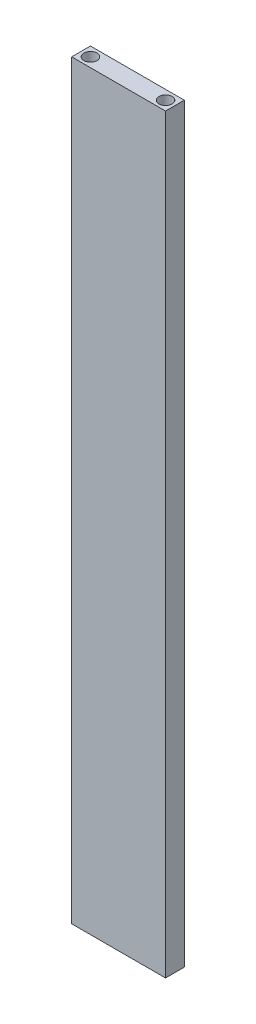
SolidWorks part; units mm, degrees
ref_plane "Front Plane" through (0, 0, 0) normal (0, 0, 1) x (1, 0, 0)
ref_plane "Top Plane" through (0, 0, 0) normal (0, 1, 0) x (1, 0, 0)
ref_plane "Right Plane" through (0, 0, 0) normal (1, 0, 0) x (0, 0, -1)
sketch "Sketch1" plane through (0, 0, 0) normal (0, 1, 0) x (1, 0, 0)
  line L1 (0, 0) -> (-20, 0)
  line L2 (0, 0) -> (0, -4)
  line L3 (0, -4) -> (-20, -4)
  line L4 (-20, 0) -> (-20, -4)
  dimension "D1" = 20
  dimension "D2" = 4
extrude "Boss-Extrude1" add sketch "Sketch1" along normal blind 160
sketch "Sketch2" plane through (0, 0, 0) normal (0, -1, 0) x (-1, 0, 0)
  line L0 (20, 0) -> (20, -4) construction
  line L1 (18, -2) -> (2, -2) construction
  line L2 (0, 0) -> (20, 0) construction
  line L3 (20, -4) -> (0, -4) construction
  circle A0 centre (18, -2) radius 1.4
  circle A1 centre (2, -2) radius 1.4
  dimension "D1" = 2.8
  dimension "D2" = 16
  dimension "D3" = 2
extrude "Cut-Extrude1" cut sketch "Sketch2" against normal up to next
